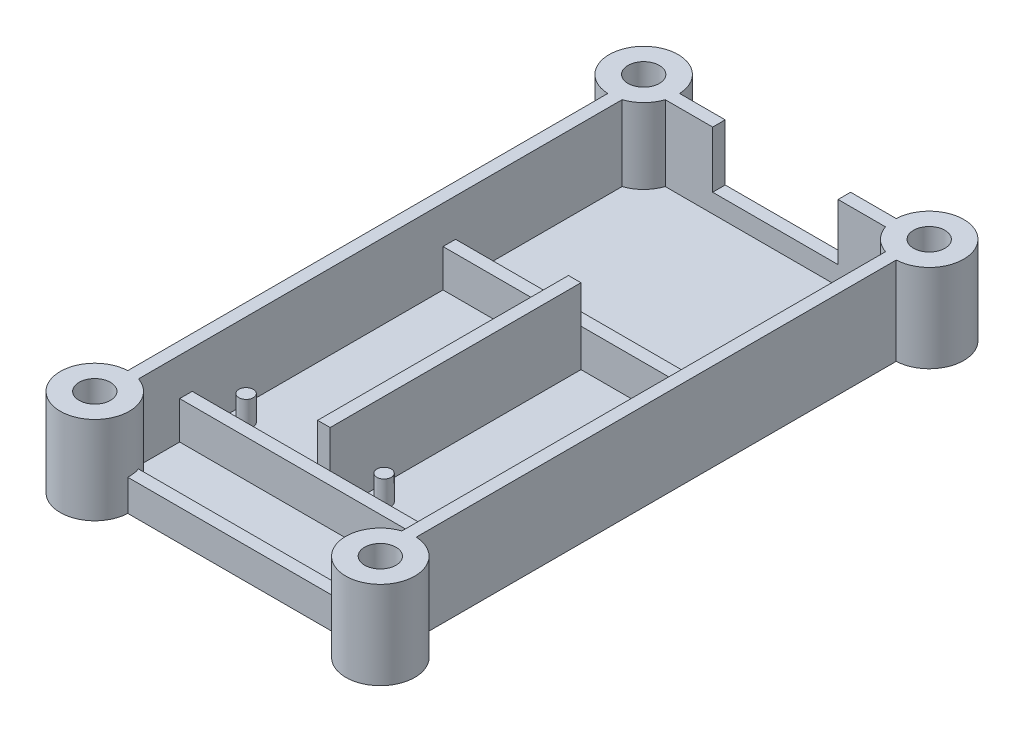
SolidWorks part; units mm, degrees
ref_plane "Front Plane" through (0, 0, 0) normal (0, 0, 1) x (1, 0, 0)
ref_plane "Top Plane" through (0, 0, 0) normal (0, 1, 0) x (1, 0, 0)
ref_plane "Right Plane" through (0, 0, 0) normal (1, 0, 0) x (0, 0, -1)
sketch "Sketch1" plane through (0, 0, 0) normal (0, 1, 0) x (1, 0, 0)
  line L0 (0, 76.6523) -> (0, -58.1633) construction
  line L5 (-26.67, -25.4) -> (-1.27, -25.4)
  line L6 (-26.67, -25.4) -> (-26.67, 25.4)
  line L7 (-26.67, 25.4) -> (-1.27, 25.4)
  line L8 (-1.27, -25.4) -> (-1.27, 25.4)
  line L17 (-29.21, 27.94) -> (-29.21, -27.94)
  line L18 (-29.21, -27.94) -> (29.21, -27.94)
  line L19 (29.21, -27.94) -> (29.21, 27.94)
  line L20 (29.21, 27.94) -> (-29.21, 27.94)
  line L21 (26.67, 25.4) -> (1.27, 25.4)
  line L22 (1.27, -25.4) -> (1.27, 25.4)
  line L23 (26.67, -25.4) -> (1.27, -25.4)
  line L24 (26.67, -25.4) -> (26.67, 25.4)
  line L33 (-29.21, 27.94) -> (29.21, 27.94)
  line L34 (-29.21, -27.94) -> (29.21, -27.94)
  line L35 (-29.21, -27.94) -> (-29.21, -35.9063)
  line L36 (-29.21, -27.94) -> (29.21, -27.94)
  line L37 (-29.21, -43.18) -> (-25.7538, -43.18)
  line L38 (29.21, -27.94) -> (29.21, -35.9063)
  line L39 (-26.67, -27.94) -> (26.67, -27.94)
  line L42 (-29.21, 0) -> (29.21, 0) construction
  line L43 (-26.67, -27.94) -> (-26.67, -36.2707)
  line L44 (-22.3007, -40.64) -> (22.3007, -40.64)
  line L45 (26.67, -27.94) -> (26.67, -36.2707)
  line L46 (26.67, 66.04) -> (29.21, 68.58) construction
  line L47 (-26.67, 27.94) -> (26.67, 27.94)
  line L48 (-29.21, 27.94) -> (29.21, 27.94)
  line L49 (-26.67, 27.94) -> (-26.67, 61.6707)
  line L54 (-26.67, -25.4) -> (-26.67, -27.94)
  line L55 (26.67, -27.94) -> (26.67, -25.4)
  line L56 (26.67, 25.4) -> (26.67, 27.94)
  line L57 (-26.67, 25.4) -> (-26.67, 27.94)
  line L58 (-1.27, 25.4) -> (1.27, 25.4)
  line L59 (1.27, -25.4) -> (-1.27, -25.4)
  line L60 (-22.3007, 66.04) -> (22.3007, 66.04)
  line L61 (26.67, 27.94) -> (26.67, 61.6707)
  line L62 (-29.21, 27.94) -> (29.21, 27.94)
  line L63 (-29.21, 27.94) -> (-29.21, 61.3063)
  line L64 (-29.21, 68.58) -> (-25.7538, 68.58)
  line L65 (29.21, 27.94) -> (29.21, 61.3063)
  line L66 (26.67, -40.64) -> (29.21, -43.18) construction
  line L67 (-21.9363, 68.58) -> (21.9363, 68.58)
  line L68 (-29.21, 65.1238) -> (-29.21, 68.58)
  line L69 (25.7538, 68.58) -> (29.21, 68.58)
  line L70 (29.21, 65.1238) -> (29.21, 68.58)
  line L71 (25.7538, -43.18) -> (29.21, -43.18)
  line L72 (29.21, -39.7238) -> (29.21, -43.18)
  line L73 (-21.9363, -43.18) -> (21.9363, -43.18)
  line L74 (-29.21, -39.7238) -> (-29.21, -43.18)
  line L75 (22.3007, 66.04) -> (26.67, 66.04) construction
  line L76 (26.67, 66.04) -> (26.67, 61.6707) construction
  line L77 (26.67, -36.2707) -> (26.67, -40.64) construction
  line L78 (26.67, -40.64) -> (22.3007, -40.64) construction
  circle A0 centre (-23.368, -17.78) radius 1.4605
  circle A1 centre (-4.6736, 16.637) radius 1.4605
  circle A2 centre (23.2664, 16.637) radius 1.4605
  circle A3 centre (4.572, -17.78) radius 1.4605
  circle A4 centre (28.9151, 68.2851) radius 3.175
  circle A5 centre (-28.9151, 68.2851) radius 3.175
  circle A6 centre (28.9151, -42.8851) radius 3.175
  circle A7 centre (-28.9151, -42.8851) radius 3.175
  circle A8 centre (28.9151, 68.2851) radius 6.985
  circle A9 centre (-28.9151, 68.2851) radius 6.985
  circle A10 centre (-28.9151, -42.8851) radius 6.985
  circle A11 centre (28.9151, -42.8851) radius 6.985
  point P0 (0, 0)
  point P1 (-26.67, 0)
  point P19 (26.67, 0)
  point P21 (13.97, -25.4)
  point P22 (-1.27, 0)
  point P23 (1.27, 0)
  dimension "D15" = 2.921
  dimension "D22" = 6.35
  dimension "D2" = 50.8
  dimension "D3" = 25.4
  dimension "D4" = 2.54
  dimension "D5" = 2.54
  dimension "D6" = 2.54
  dimension "D7" = 2.54
  dimension "D8" = 2.54
  dimension "D9" = 2.54
  dimension "D10" = 12.7
  dimension "D11" = 2.54
  dimension "D12" = 2.54
  dimension "D13" = 7.62
  dimension "D14" = 3.302
  dimension "D16" = 3.302
  dimension "D17" = 34.417
  dimension "D18" = 18.6944
  dimension "D19" = 18.6944
  dimension "D20" = 2.54
  dimension "D21" = 38.1
  dimension "D27" = 45
  dimension "D23" = 3.81
  dimension "D24" = 3.81
  dimension "D25" = 3.81
  dimension "D26" = 3.81
extrude "Boss-Extrude1" add sketch "Sketch1" along normal blind 17.78 contours A10 A7 | L35 A10 L43 L18 | L6 L57 L20 L17 L18 L54 | L56 L24 L55 L18 L19 L20 | A11 L38 L18 L45 | A11 A6 | L49 A9 L63 L20 | A8 L61 L20 L65 | A9 A5 | L67 A9 L60 A8 | A8 A4 | L59 L22 L58 L8
sketch "Sketch25" plane through (0, 0, 0) normal (0, 1, 0) x (1, 0, 0)
  line L0 (26.67, -40.64) -> (22.3007, -40.64) construction
  line L1 (26.67, -36.2707) -> (26.67, -40.64) construction
  line L2 (26.67, -40.64) -> (29.21, -43.18) construction
  line L3 (29.21, -39.7238) -> (29.21, -43.18) construction
  line L4 (25.7538, -43.18) -> (29.21, -43.18) construction
  line L5 (29.21, -27.94) -> (29.21, -35.9063) construction
  line L6 (26.67, -27.94) -> (26.67, -36.2707) construction
  line L7 (-29.21, -43.18) -> (-25.7538, -43.18) construction
  line L8 (-29.21, -39.7238) -> (-29.21, -43.18) construction
  line L9 (-29.21, -27.94) -> (-29.21, -35.9063) construction
  line L10 (-26.67, -27.94) -> (-26.67, -36.2707) construction
  line L11 (-21.9363, -43.18) -> (21.9363, -43.18) construction
  line L12 (-22.3007, -40.64) -> (22.3007, -40.64) construction
  line L13 (-26.67, -25.4) -> (-1.27, -25.4) construction
  line L14 (26.67, -25.4) -> (1.27, -25.4) construction
  line L15 (-29.21, -27.94) -> (29.21, -27.94) construction
  line L16 (-29.21, 0) -> (29.21, 0) construction
  line L17 (-26.67, -25.4) -> (-26.67, 25.4) construction
  line L18 (-1.27, -25.4) -> (-1.27, 25.4) construction
  line L19 (1.27, -25.4) -> (1.27, 25.4) construction
  line L20 (26.67, 25.4) -> (26.67, 27.94) construction
  line L21 (26.67, -25.4) -> (26.67, 25.4) construction
  line L22 (29.21, -27.94) -> (29.21, 27.94) construction
  line L23 (26.67, 25.4) -> (1.27, 25.4) construction
  line L24 (-29.21, 27.94) -> (-29.21, -27.94) construction
  line L25 (-26.67, 25.4) -> (-26.67, 27.94) construction
  line L26 (-26.67, 25.4) -> (-1.27, 25.4) construction
  line L27 (29.21, 27.94) -> (-29.21, 27.94) construction
  line L28 (-29.21, 27.94) -> (-29.21, 61.3063) construction
  line L29 (-26.67, 27.94) -> (-26.67, 61.6707) construction
  line L30 (26.67, 66.04) -> (26.67, 61.6707) construction
  line L31 (22.3007, 66.04) -> (26.67, 66.04) construction
  line L32 (26.67, 27.94) -> (26.67, 61.6707) construction
  line L33 (29.21, 27.94) -> (29.21, 61.3063) construction
  line L34 (25.7538, 68.58) -> (29.21, 68.58) construction
  line L35 (29.21, 65.1238) -> (29.21, 68.58) construction
  line L36 (26.67, 66.04) -> (29.21, 68.58) construction
  line L37 (0, 76.6523) -> (0, -58.1633) construction
  line L38 (-22.3007, 66.04) -> (22.3007, 66.04) construction
  line L39 (-21.9363, 68.58) -> (21.9363, 68.58) construction
  line L40 (-29.21, 68.58) -> (-25.7538, 68.58) construction
  line L41 (-29.21, 65.1238) -> (-29.21, 68.58) construction
  line L42 (26.67, -40.64) -> (22.3007, -40.64) construction
  line L43 (26.67, -36.2707) -> (26.67, -40.64) construction
  line L44 (26.67, -40.64) -> (29.21, -43.18) construction
  line L45 (29.21, -39.7238) -> (29.21, -43.18)
  line L46 (25.7538, -43.18) -> (29.21, -43.18)
  line L47 (29.21, -27.94) -> (29.21, -35.9063)
  line L48 (26.67, -27.94) -> (26.67, -36.2707)
  line L49 (-29.21, -43.18) -> (-25.7538, -43.18)
  line L50 (-29.21, -39.7238) -> (-29.21, -43.18)
  line L51 (-29.21, -27.94) -> (-29.21, -35.9063)
  line L52 (-26.67, -27.94) -> (-26.67, -36.2707)
  line L53 (-21.9363, -43.18) -> (21.9363, -43.18)
  line L54 (-22.3007, -40.64) -> (22.3007, -40.64)
  line L55 (-26.67, -25.4) -> (-1.27, -25.4)
  line L56 (26.67, -25.4) -> (1.27, -25.4)
  line L57 (-29.21, -27.94) -> (29.21, -27.94)
  line L58 (-29.21, 0) -> (29.21, 0) construction
  line L59 (-26.67, -25.4) -> (-26.67, 25.4)
  line L60 (-1.27, -25.4) -> (-1.27, 25.4)
  line L61 (1.27, -25.4) -> (1.27, 25.4)
  line L62 (26.67, 25.4) -> (26.67, 27.94)
  line L63 (26.67, -25.4) -> (26.67, 25.4)
  line L64 (29.21, -27.94) -> (29.21, 27.94)
  line L65 (26.67, 25.4) -> (1.27, 25.4)
  line L66 (-29.21, 27.94) -> (-29.21, -27.94)
  line L67 (-26.67, 25.4) -> (-26.67, 27.94)
  line L68 (-26.67, 25.4) -> (-1.27, 25.4)
  line L69 (29.21, 27.94) -> (-29.21, 27.94)
  line L70 (-29.21, 27.94) -> (-29.21, 61.3063)
  line L71 (-26.67, 27.94) -> (-26.67, 61.6707)
  line L72 (26.67, 66.04) -> (26.67, 61.6707) construction
  line L73 (22.3007, 66.04) -> (26.67, 66.04) construction
  line L74 (26.67, 27.94) -> (26.67, 61.6707)
  line L75 (29.21, 27.94) -> (29.21, 61.3063)
  line L76 (25.7538, 68.58) -> (29.21, 68.58) construction
  line L77 (29.21, 65.1238) -> (29.21, 68.58) construction
  line L78 (26.67, 66.04) -> (29.21, 68.58) construction
  line L79 (0, 76.6523) -> (0, -58.1633) construction
  line L80 (-22.3007, 66.04) -> (22.3007, 66.04)
  line L81 (-21.9363, 68.58) -> (21.9363, 68.58)
  line L82 (-29.21, 68.58) -> (-25.7538, 68.58)
  line L83 (-29.21, 65.1238) -> (-29.21, 68.58)
  circle A0 centre (28.9151, -42.8851) radius 3.175 construction
  circle A1 centre (28.9151, -42.8851) radius 6.985 construction
  circle A2 centre (-28.9151, -42.8851) radius 3.175 construction
  circle A3 centre (-28.9151, -42.8851) radius 6.985 construction
  circle A4 centre (23.2664, 16.637) radius 1.4605 construction
  circle A5 centre (-23.368, -17.78) radius 1.4605 construction
  circle A6 centre (-4.6736, 16.637) radius 1.4605 construction
  circle A7 centre (28.9151, 68.2851) radius 3.175 construction
  circle A8 centre (28.9151, 68.2851) radius 6.985 construction
  circle A9 centre (-28.9151, 68.2851) radius 6.985 construction
  circle A10 centre (28.9151, -42.8851) radius 3.175
  circle A11 centre (28.9151, -42.8851) radius 6.985
  circle A12 centre (-28.9151, -42.8851) radius 3.175
  circle A13 centre (-28.9151, -42.8851) radius 6.985
  circle A14 centre (23.2664, 16.637) radius 1.4605
  circle A15 centre (-23.368, -17.78) radius 1.4605
  circle A16 centre (-4.6736, 16.637) radius 1.4605
  circle A17 centre (28.9151, 68.2851) radius 3.175
  circle A18 centre (28.9151, 68.2851) radius 6.985
  circle A19 centre (-28.9151, 68.2851) radius 6.985
  circle A20 centre (4.572, -17.78) radius 1.4605 construction
  circle A21 centre (-28.9151, 68.2851) radius 3.175 construction
  circle A22 centre (4.572, -17.78) radius 1.4605
  circle A23 centre (-28.9151, 68.2851) radius 3.175
  point P0 (-26.67, 61.6707)
sketch "Sketch16" plane through (0, 0, 0) normal (0, 1, 0) x (1, 0, 0)
  line L0 (0, 63.9928) -> (0, -58.1633) construction
  line L5 (-26.67, -25.4) -> (-1.27, -25.4)
  line L6 (-26.67, -25.4) -> (-26.67, 25.4)
  line L7 (-26.67, 25.4) -> (-1.27, 25.4)
  line L8 (-1.27, -25.4) -> (-1.27, 25.4)
  line L17 (-29.21, 27.94) -> (-29.21, -27.94)
  line L18 (-29.21, -27.94) -> (29.21, -27.94)
  line L19 (29.21, -27.94) -> (29.21, 27.94)
  line L20 (29.21, 27.94) -> (-29.21, 27.94)
  line L21 (26.67, 25.4) -> (1.27, 25.4)
  line L22 (1.27, -25.4) -> (1.27, 25.4)
  line L23 (26.67, -25.4) -> (1.27, -25.4)
  line L24 (26.67, -25.4) -> (26.67, 25.4)
  line L33 (-29.21, 27.94) -> (29.21, 27.94)
  line L34 (-29.21, -27.94) -> (29.21, -27.94)
  line L35 (-29.21, -27.94) -> (-29.21, -43.18)
  line L36 (-29.21, -27.94) -> (29.21, -27.94)
  line L37 (-29.21, -43.18) -> (29.21, -43.18)
  line L38 (29.21, -27.94) -> (29.21, -43.18)
  line L39 (-26.67, -27.94) -> (26.67, -27.94)
  line L42 (-29.21, 0) -> (29.21, 0) construction
  line L43 (-26.67, -27.94) -> (-26.67, -40.64)
  line L44 (-26.67, -40.64) -> (26.67, -40.64)
  line L45 (26.67, -27.94) -> (26.67, -40.64)
  line L46 (-29.21, 43.18) -> (29.21, 43.18)
  line L47 (29.21, 27.94) -> (29.21, 43.18)
  line L48 (-29.21, 27.94) -> (29.21, 27.94)
  line L49 (-29.21, 27.94) -> (-29.21, 43.18)
  line L50 (-26.67, 40.64) -> (26.67, 40.64)
  line L51 (26.67, 27.94) -> (26.67, 40.64)
  line L52 (-26.67, 27.94) -> (26.67, 27.94)
  line L53 (-26.67, 27.94) -> (-26.67, 40.64)
  line L54 (-26.67, -25.4) -> (-26.67, -27.94)
  line L55 (26.67, -27.94) -> (26.67, -25.4)
  line L56 (26.67, 25.4) -> (26.67, 27.94)
  line L57 (-26.67, 25.4) -> (-26.67, 27.94)
  line L58 (-1.27, 25.4) -> (1.27, 25.4)
  line L59 (1.27, -25.4) -> (-1.27, -25.4)
  circle A0 centre (-23.368, -17.78) radius 1.4605
  circle A1 centre (-4.6736, 16.637) radius 1.4605
  circle A2 centre (23.2664, 16.637) radius 1.4605
  circle A3 centre (4.572, -17.78) radius 1.4605
  point P0 (0, 0)
  point P1 (-26.67, 0)
  point P19 (26.67, 0)
  point P21 (13.97, -25.4)
  point P22 (-1.27, 0)
  point P23 (1.27, 0)
  point P44 (0, -1.5571)
  dimension "D15" = 2.921
  dimension "D2" = 50.8
  dimension "D3" = 25.4
  dimension "D4" = 2.54
  dimension "D5" = 2.54
  dimension "D6" = 2.54
  dimension "D7" = 2.54
  dimension "D8" = 2.54
  dimension "D9" = 2.54
  dimension "D10" = 12.7
  dimension "D11" = 2.54
  dimension "D12" = 2.54
  dimension "D13" = 7.62
  dimension "D14" = 3.302
  dimension "D16" = 3.302
  dimension "D17" = 34.417
  dimension "D18" = 18.6944
  dimension "D19" = 18.6944
sketch "Sketch17" plane through (0, 0, 0) normal (0, 1, 0) x (1, 0, 0)
  line L0 (0, 63.9928) -> (0, -58.1633) construction
  line L5 (-26.67, -25.4) -> (-1.27, -25.4)
  line L6 (-26.67, -25.4) -> (-26.67, 25.4)
  line L7 (-26.67, 25.4) -> (-1.27, 25.4)
  line L8 (-1.27, -25.4) -> (-1.27, 25.4)
  line L17 (-29.21, 27.94) -> (-29.21, -27.94)
  line L18 (-29.21, -27.94) -> (29.21, -27.94)
  line L19 (29.21, -27.94) -> (29.21, 27.94)
  line L20 (29.21, 27.94) -> (-29.21, 27.94)
  line L21 (26.67, 25.4) -> (1.27, 25.4)
  line L22 (1.27, -25.4) -> (1.27, 25.4)
  line L23 (26.67, -25.4) -> (1.27, -25.4)
  line L24 (26.67, -25.4) -> (26.67, 25.4)
  line L33 (-29.21, 27.94) -> (29.21, 27.94)
  line L34 (-29.21, -27.94) -> (29.21, -27.94)
  line L35 (-29.21, -27.94) -> (-29.21, -43.18)
  line L36 (-29.21, -27.94) -> (29.21, -27.94)
  line L37 (-29.21, -43.18) -> (29.21, -43.18)
  line L38 (29.21, -27.94) -> (29.21, -43.18)
  line L39 (-26.67, -27.94) -> (26.67, -27.94)
  line L42 (-29.21, 0) -> (29.21, 0) construction
  line L43 (-26.67, -27.94) -> (-26.67, -40.64)
  line L44 (-26.67, -40.64) -> (26.67, -40.64)
  line L45 (26.67, -27.94) -> (26.67, -40.64)
  line L46 (-29.21, 43.18) -> (29.21, 43.18)
  line L47 (29.21, 27.94) -> (29.21, 43.18)
  line L48 (-29.21, 27.94) -> (29.21, 27.94)
  line L49 (-29.21, 27.94) -> (-29.21, 43.18)
  line L50 (-26.67, 40.64) -> (26.67, 40.64)
  line L51 (26.67, 27.94) -> (26.67, 40.64)
  line L52 (-26.67, 27.94) -> (26.67, 27.94)
  line L53 (-26.67, 27.94) -> (-26.67, 40.64)
  line L54 (-26.67, -25.4) -> (-26.67, -27.94)
  line L55 (26.67, -27.94) -> (26.67, -25.4)
  line L56 (26.67, 25.4) -> (26.67, 27.94)
  line L57 (-26.67, 25.4) -> (-26.67, 27.94)
  line L58 (-1.27, 25.4) -> (1.27, 25.4)
  line L59 (1.27, -25.4) -> (-1.27, -25.4)
  circle A0 centre (-23.368, -17.78) radius 1.4605
  circle A1 centre (-4.6736, 16.637) radius 1.4605
  circle A2 centre (23.622, 16.637) radius 1.4605
  circle A3 centre (4.572, -17.78) radius 1.4605
  point P0 (0, 0)
  point P1 (-26.67, 0)
  point P19 (26.67, 0)
  point P21 (13.97, -25.4)
  point P22 (-1.27, 0)
  point P23 (1.27, 0)
  dimension "D15" = 2.921
  dimension "D2" = 50.8
  dimension "D3" = 25.4
  dimension "D4" = 2.54
  dimension "D5" = 2.54
  dimension "D6" = 2.54
  dimension "D7" = 2.54
  dimension "D8" = 2.54
  dimension "D9" = 2.54
  dimension "D10" = 12.7
  dimension "D11" = 2.54
  dimension "D12" = 2.54
  dimension "D13" = 7.62
  dimension "D14" = 3.302
  dimension "D16" = 3.302
  dimension "D17" = 34.417
  dimension "D18" = 18.6944
  dimension "D19" = 19.05
extrude "Boss-Extrude10" add sketch "Sketch25" along normal blind 2.54 separate body contours L68 L59 L55 L60 A16 A15 | L63 L65 L61 L56 A22 A14 | A19 L71 L69 L74 A18 L80 | A13 L54 A11 L48 L57 L52
extrude "Boss-Extrude8" add sketch "Sketch16" along normal blind 7.62 contours A1 | A0 | A3 | A2
extrude "Boss-Extrude9" add sketch "Sketch17" along normal blind 10.16 contours L23 L59 L5 L54 L36 L55 | L7 L58 L21 L56 L48 L57 | L20
sketch "Sketch27" plane through (0, 0, 0) normal (0, 1, 0) x (1, 0, 0)
  line L0 (0, 76.6523) -> (0, -58.1633) construction
  line L5 (-26.67, -25.4) -> (-1.27, -25.4)
  line L6 (-26.67, -25.4) -> (-26.67, 25.4)
  line L7 (-26.67, 25.4) -> (-1.27, 25.4)
  line L8 (-1.27, -25.4) -> (-1.27, 25.4)
  line L17 (-29.21, 27.94) -> (-29.21, -27.94)
  line L18 (-29.21, -27.94) -> (29.21, -27.94)
  line L19 (29.21, -27.94) -> (29.21, 27.94)
  line L20 (29.21, 27.94) -> (-29.21, 27.94)
  line L21 (26.67, 25.4) -> (1.27, 25.4)
  line L22 (1.27, -25.4) -> (1.27, 25.4)
  line L23 (26.67, -25.4) -> (1.27, -25.4)
  line L24 (26.67, -25.4) -> (26.67, 25.4)
  line L33 (-29.21, 27.94) -> (29.21, 27.94)
  line L34 (-29.21, -27.94) -> (29.21, -27.94)
  line L35 (-29.21, -27.94) -> (-29.21, -35.9063)
  line L36 (-29.21, -27.94) -> (29.21, -27.94)
  line L37 (-29.21, -43.18) -> (-25.7538, -43.18)
  line L38 (29.21, -27.94) -> (29.21, -35.9063)
  line L39 (-26.67, -27.94) -> (26.67, -27.94)
  line L42 (-29.21, 0) -> (29.21, 0) construction
  line L43 (-26.67, -27.94) -> (-26.67, -36.2707)
  line L44 (-22.3007, -40.64) -> (22.3007, -40.64)
  line L45 (26.67, -27.94) -> (26.67, -36.2707)
  line L46 (26.67, 66.04) -> (29.21, 68.58) construction
  line L47 (-26.67, 27.94) -> (26.67, 27.94)
  line L48 (-29.21, 27.94) -> (29.21, 27.94)
  line L49 (-26.67, 27.94) -> (-26.67, 61.6707)
  line L54 (-26.67, -25.4) -> (-26.67, -27.94)
  line L55 (26.67, -27.94) -> (26.67, -25.4)
  line L56 (26.67, 25.4) -> (26.67, 27.94)
  line L57 (-26.67, 25.4) -> (-26.67, 27.94)
  line L58 (-1.27, 25.4) -> (1.27, 25.4)
  line L59 (1.27, -25.4) -> (-1.27, -25.4)
  line L60 (-22.3007, 66.04) -> (22.3007, 66.04)
  line L61 (26.67, 27.94) -> (26.67, 61.6707)
  line L62 (-29.21, 27.94) -> (29.21, 27.94)
  line L63 (-29.21, 27.94) -> (-29.21, 61.3063)
  line L64 (-29.21, 68.58) -> (-25.7538, 68.58)
  line L65 (29.21, 27.94) -> (29.21, 61.3063)
  line L66 (26.67, -40.64) -> (29.21, -43.18) construction
  line L67 (-21.9363, 68.58) -> (21.9363, 68.58)
  line L68 (-29.21, 65.1238) -> (-29.21, 68.58)
  line L69 (25.7538, 68.58) -> (29.21, 68.58)
  line L70 (29.21, 65.1238) -> (29.21, 68.58)
  line L71 (25.7538, -43.18) -> (29.21, -43.18)
  line L72 (29.21, -39.7238) -> (29.21, -43.18)
  line L73 (-21.9363, -43.18) -> (21.9363, -43.18)
  line L74 (-29.21, -39.7238) -> (-29.21, -43.18)
  line L75 (22.3007, 66.04) -> (26.67, 66.04) construction
  line L76 (26.67, 66.04) -> (26.67, 61.6707) construction
  line L77 (26.67, -36.2707) -> (26.67, -40.64) construction
  line L78 (26.67, -40.64) -> (22.3007, -40.64) construction
  circle A0 centre (-23.368, -17.78) radius 1.4605
  circle A1 centre (-4.6736, 16.637) radius 1.4605
  circle A2 centre (23.2664, 16.637) radius 1.4605
  circle A3 centre (4.572, -17.78) radius 1.4605
  circle A4 centre (28.9151, 68.2851) radius 3.175
  circle A5 centre (-28.9151, 68.2851) radius 3.175
  circle A6 centre (28.9151, -42.8851) radius 3.175
  circle A7 centre (-28.9151, -42.8851) radius 3.175
  circle A8 centre (28.9151, 68.2851) radius 6.985
  circle A9 centre (-28.9151, 68.2851) radius 6.985
  circle A10 centre (-28.9151, -42.8851) radius 6.985
  circle A11 centre (28.9151, -42.8851) radius 6.985
  point P0 (0, 0)
extrude "Boss-Extrude11" add sketch "Sketch27" along normal blind 6.35 contours A11 L44 A10 L73
sketch "Sketch20" plane through (0, 0, -68.58) normal (0, 0, -1) x (-1, 0, 0)
  line L5 (-12.7, 17.78) -> (12.7, 17.78)
  line L6 (-12.7, 17.78) -> (-12.7, 6.35)
  line L7 (-12.7, 6.35) -> (12.7, 6.35)
  line L8 (12.7, 17.78) -> (12.7, 6.35)
  line L10 (21.9363, 17.78) -> (-21.9363, 17.78) construction
  point P4 (0, 17.78)
  point P5 (0, 17.78)
  dimension "D1" = 25.4
  dimension "D2" = 11.43
extrude "Cut-Extrude7" cut sketch "Sketch20" against normal up to next (2.54 mm away)
